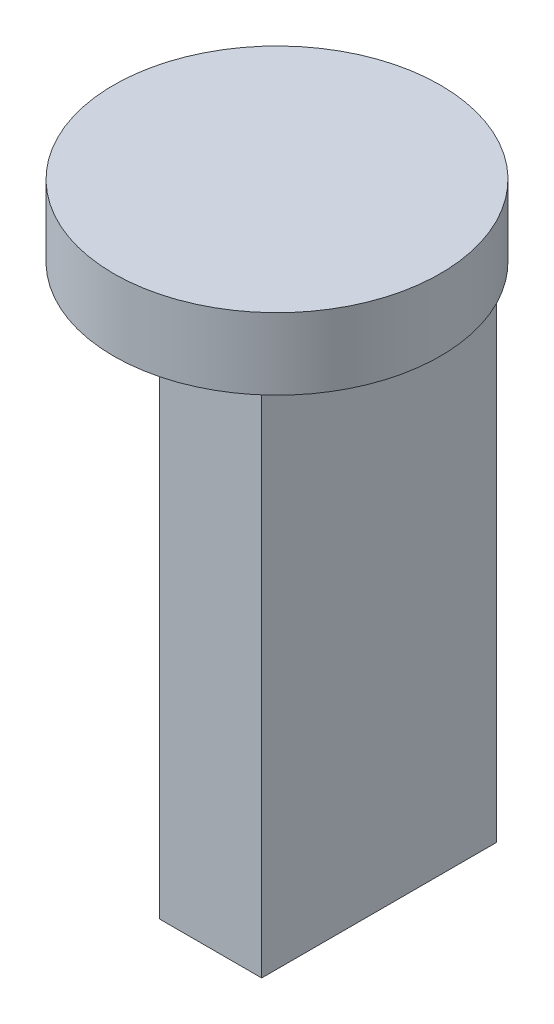
SolidWorks part; units mm, degrees
ref_plane "Alzado" through (0, 0, 0) normal (0, 0, 1) x (1, 0, 0)
ref_plane "Planta" through (0, 0, 0) normal (0, 1, 0) x (1, 0, 0)
ref_plane "Vista lateral" through (0, 0, 0) normal (1, 0, 0) x (0, 0, -1)
sketch "Croquis1" plane through (0, 0, 0) normal (0, 1, 0) x (1, 0, 0)
  line L1 (-25, -57.5) -> (25, -57.5)
  line L2 (-25, -57.5) -> (-25, 57.5)
  line L3 (-25, 57.5) -> (25, 57.5)
  line L4 (25, -57.5) -> (25, 57.5)
  line L5 (-25, -57.5) -> (25, 57.5) construction
  line L6 (-25, 57.5) -> (25, -57.5) construction
  line L7 (-25, 25) -> (-40, 25)
  line L8 (-25, 25) -> (-25, -25)
  line L9 (-25, -25) -> (-40, -25)
  line L10 (-40, 25) -> (-40, -25)
  point P0 (0, 0)
  point P10 (-40, 0)
  point P11 (0, 0)
  dimension "D1" = 50
  dimension "D2" = 115
  dimension "D3" = 50
  dimension "D4" = 15
extrude "Saliente-Extruir1" add sketch "Croquis1" along normal blind 250 contours L7 L10 L9 L2 | L1 L4 L3 L2
sketch "Croquis2" plane through (0, 250, 0) normal (0, 1, 0) x (1, 0, 0)
  line L0 (-25, 25) -> (-25, -25) construction
  circle A0 centre (-25, 0) radius 80
  dimension "D1" = 160
extrude "Saliente-Extruir2" add sketch "Croquis2" along normal blind 35
